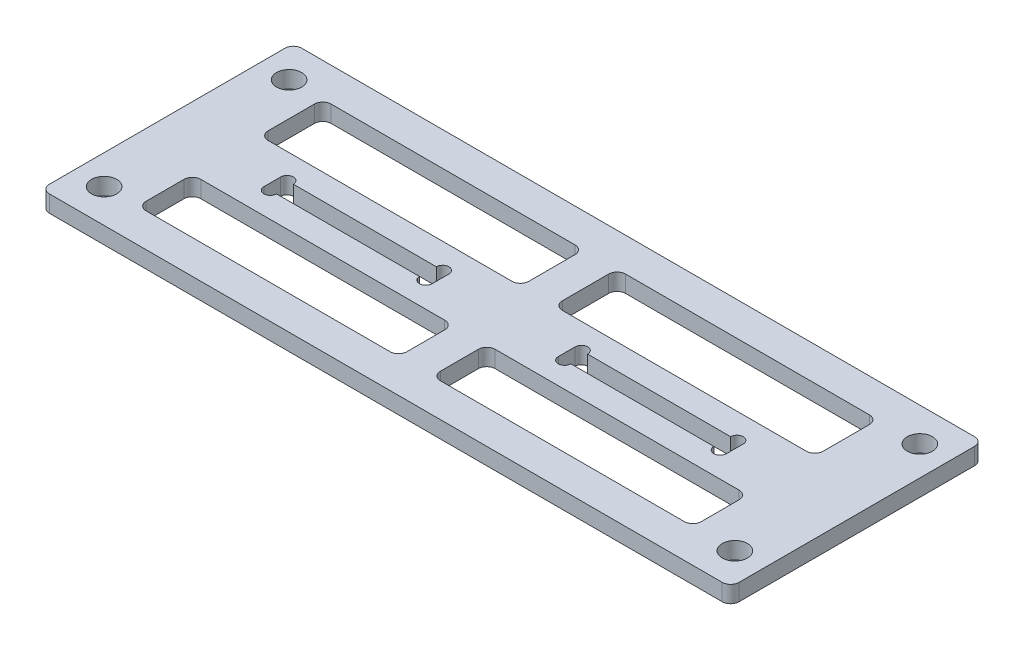
SolidWorks part; units mm, degrees
material "Thornel Mat VMA"
ref_plane "前视基准面" through (0, 0, 0) normal (0, 0, 1) x (1, 0, 0)
ref_plane "上视基准面" through (0, 0, 0) normal (0, 1, 0) x (1, 0, 0)
ref_plane "右视基准面" through (0, 0, 0) normal (1, 0, 0) x (0, 0, -1)
sketch "草图1" plane through (0, 0, 0) normal (0, 1, 0) x (1, 0, 0)
  line L27 (-37.5, 26) -> (-37.5, 4) construction
  line L28 (-37.5, 26) -> (37.5, 26) construction
  line L29 (-37.5, 4) -> (37.5, 4) construction
  line L30 (37.5, 26) -> (37.5, 4) construction
  line L38 (-41, 30) -> (41, 30)
  line L39 (-41, 30) -> (-41, 0)
  line L40 (-41, 0) -> (41, 0)
  line L41 (41, 30) -> (41, 0)
  line L50 (7, 13.5) -> (27, 13.5)
  line L51 (27, 13.5) -> (27, 15.5)
  line L52 (27, 15.5) -> (7, 15.5)
  line L53 (7, 15.5) -> (7, 13.5)
  line L54 (-28, 13.5) -> (-8, 13.5)
  line L55 (-8, 13.5) -> (-8, 15.5)
  line L56 (-8, 15.5) -> (-28, 15.5)
  line L57 (-28, 15.5) -> (-28, 13.5)
  circle A1 centre (-37.5, 26) radius 1.5
  circle A2 centre (-37.5, 4) radius 1.5
  circle A3 centre (37.5, 26) radius 1.5
  circle A4 centre (37.5, 4) radius 1.5
  point P5 (0, 30)
  point P10 (0, 26)
  dimension "D15" = 3
  dimension "D5" = 75
  dimension "D2" = 4
  dimension "D3" = 4
  dimension "D4" = 82
  dimension "D9" = 22
  dimension "D11" = 20
  dimension "D12" = 15
  dimension "D13" = 13
  dimension "D14" = 14.5
  dimension "D16" = 2
extrude "凸台-拉伸1" add sketch "草图1" along normal blind 2
sketch "草图4" plane through (0, 2, 0) normal (0, 1, 0) x (1, 0, 0)
  line L0 (-8, 15.5) -> (-28, 15.5) construction
  line L1 (-28, 13.5) -> (-8, 13.5) construction
  line L3 (27, 15.5) -> (7, 15.5) construction
  line L4 (7, 13.5) -> (27, 13.5) construction
  circle A0 centre (-27.25, 15.5) radius 0.75
  circle A1 centre (-27.25, 13.5) radius 0.75
  circle A2 centre (-8.75, 15.5) radius 0.75
  circle A3 centre (-8.75, 13.5) radius 0.75
  circle A4 centre (7.75, 15.5) radius 0.75
  circle A5 centre (7.75, 13.5) radius 0.75
  circle A6 centre (26.25, 15.5) radius 0.75
  circle A7 centre (26.25, 13.5) radius 0.75
  dimension "D1" = 1.5
extrude "切除-拉伸1" cut sketch "草图4" against normal through all
sketch "草图5" plane through (0, 2, 0) normal (0, 1, 0) x (1, 0, 0)
  line L0 (-8, 14.5) -> (7, 14.5) construction
  line L1 (-33.5, 10.5) -> (-2.5, 10.5)
  line L2 (-33.5, 10.5) -> (-33.5, 4)
  line L3 (-33.5, 4) -> (-2.5, 4)
  line L4 (-2.5, 10.5) -> (-2.5, 4)
  line L5 (-33.5, 26) -> (-2.5, 26)
  line L6 (-33.5, 26) -> (-33.5, 18.5)
  line L7 (-33.5, 18.5) -> (-2.5, 18.5)
  line L8 (-2.5, 26) -> (-2.5, 18.5)
  line L9 (-8, 13.5) -> (-8, 15.5) construction
  line L10 (7, 15.5) -> (7, 13.5) construction
  line L11 (-0.5, 14.5) -> (-0.5, 27.2781) construction
  line L12 (1.5, 26) -> (1.5, 18.5)
  line L13 (32.5, 18.5) -> (1.5, 18.5)
  line L14 (32.5, 26) -> (32.5, 18.5)
  line L15 (32.5, 26) -> (1.5, 26)
  line L16 (1.5, 10.5) -> (1.5, 4)
  line L17 (32.5, 4) -> (1.5, 4)
  line L18 (32.5, 10.5) -> (32.5, 4)
  line L19 (32.5, 10.5) -> (1.5, 10.5)
  line L20 (41, 30) -> (-41, 30) construction
  line L21 (-9.5, 15.5) -> (-26.5, 15.5) construction
  line L22 (-26.5, 13.5) -> (-9.5, 13.5) construction
  line L23 (-41, 0) -> (41, 0) construction
  circle A0 centre (-37.5, 26) radius 1.5 construction
  dimension "D3" = 4
  dimension "D1" = 4
  dimension "D2" = 4
  dimension "D4" = 3
  dimension "D5" = 3
  dimension "D6" = 4
extrude "切除-拉伸2" cut sketch "草图5" against normal through all
fillet "圆角1" radius 1 20 edges at (41, 1, -30) (41, 1, 0) (-33.5, 1, -4) (-2.5, 1, -4) (-2.5, 1, -10.5) (-33.5, 1, -10.5) (-33.5, 1, -18.5) (-2.5, 1, -18.5) (-2.5, 1, -26) (-33.5, 1, -26) (1.5, 1, -26) (1.5, 1, -18.5) (32.5, 1, -18.5) (32.5, 1, -26) (1.5, 1, -10.5) (1.5, 1, -4) (32.5, 1, -4) (32.5, 1, -10.5) (-41, 1, 0) (-41, 1, -30)
